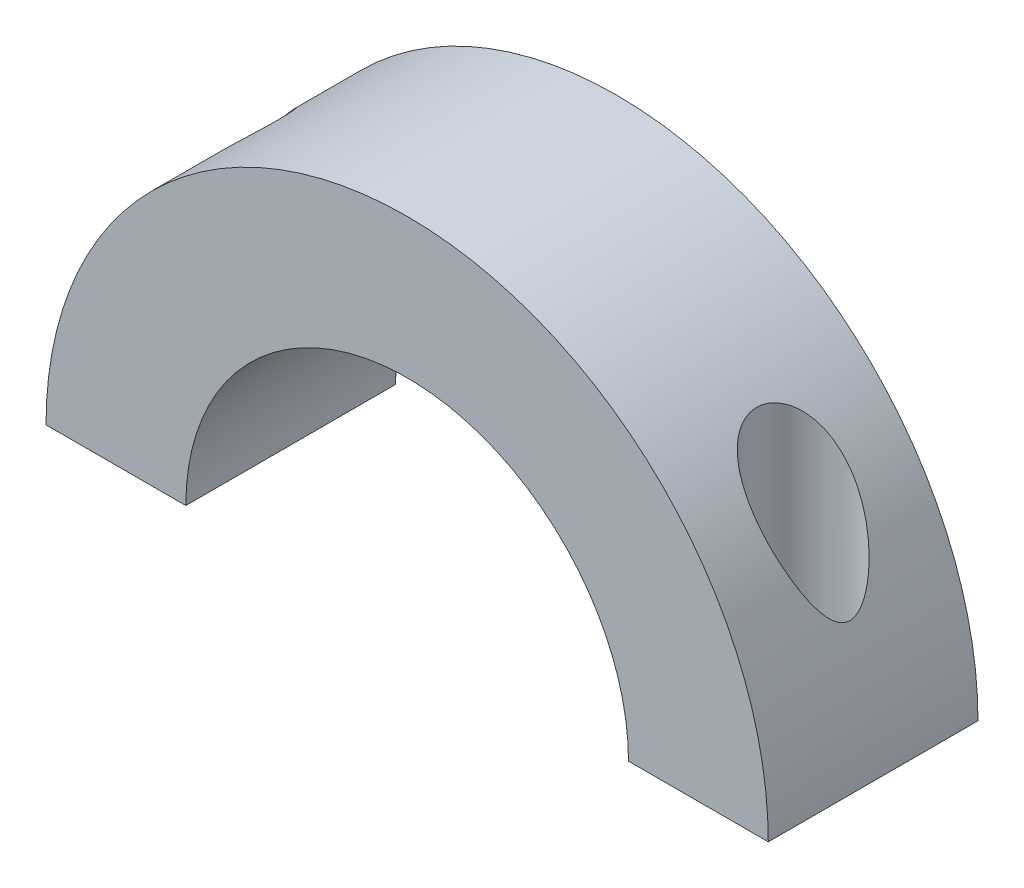
SolidWorks part; units mm, degrees
ref_plane "Front Plane" through (0, 0, 0) normal (0, 0, 1) x (1, 0, 0)
ref_plane "Top Plane" through (0, 0, 0) normal (0, 1, 0) x (1, 0, 0)
ref_plane "Right Plane" through (0, 0, 0) normal (1, 0, 0) x (0, 0, -1)
sketch "Sketch1" plane through (0, 0, 0) normal (0, 0, 1) x (1, 0, 0)
  line L0 (-31, 0) -> (-19, 0)
  line L1 (19, 0) -> (31, 0)
  arc A0 (19, 0) -> (-19, 0) centre (0, 0) ccw
  arc A1 (31, 0) -> (-31, 0) centre (0, 0) ccw
  point P7 (0, 0)
  dimension "D1" = 38
  dimension "D2" = 12
extrude "Boss-Extrude1" add sketch "Sketch1" along normal blind 18
sketch "Sketch2" plane through (0, 0, 0) normal (0, -1, 0) x (1, 0, 0)
  line L0 (-31, 9) -> (31, 9) construction
  line L1 (-31, 18) -> (-31, 0) construction
  line L2 (31, 18) -> (31, 0) construction
  line L3 (-24.166, 18) -> (-24.166, 0) construction
  line L4 (-31, 18) -> (-19, 18) construction
  line L5 (-31, 0) -> (-19, 0) construction
  line L6 (25, 0) -> (25, 18) construction
  line L7 (19, 0) -> (31, 0) construction
  line L8 (19, 18) -> (31, 18) construction
  circle A0 centre (-24.166, 9) radius 2
  circle A1 centre (25, 9) radius 2
  dimension "D1" = 4
extrude "Cut-Extrude1" cut sketch "Sketch2" against normal through all
ref_plane "Plane1" through (0, 6, 0) normal (0, 1, 0) x (1, 0, 0)
sketch "Sketch3" plane through (0, 6, 0) normal (0, 1, 0) x (1, 0, 0)
  circle A0 centre (-24.166, -9) radius 4
  circle A1 centre (25, -9) radius 4
  dimension "D1" = 8
extrude "Cut-Extrude2" cut sketch "Sketch3" along normal through all
ref_plane "Plane2" through (0, 0, 9) normal (0, 0, 1) x (1, 0, 0)
